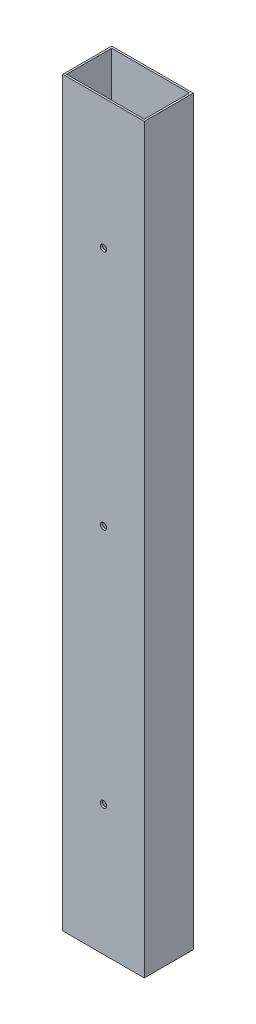
SolidWorks part; units mm, degrees
material "6061 Alloy"
ref_plane "Front Plane" through (0, 0, 0) normal (0, 0, 1) x (1, 0, 0)
ref_plane "Top Plane" through (0, 0, 0) normal (0, 1, 0) x (1, 0, 0)
ref_plane "Right Plane" through (0, 0, 0) normal (1, 0, 0) x (0, 0, -1)
sketch "Sketch1" plane through (0, 0, 0) normal (0, 1, 0) x (1, 0, 0)
  line L0 (-24.2, 14.05) -> (24.2, 14.05)
  line L1 (-25.4, -15.25) -> (25.4, -15.25)
  line L2 (-25.4, -15.25) -> (-25.4, 15.25)
  line L3 (-25.4, 15.25) -> (25.4, 15.25)
  line L4 (25.4, -15.25) -> (25.4, 15.25)
  line L5 (-25.4, -15.25) -> (25.4, 15.25) construction
  line L6 (-25.4, 15.25) -> (25.4, -15.25) construction
  line L7 (24.2, -14.05) -> (24.2, 14.05)
  line L8 (-24.2, -14.05) -> (24.2, -14.05)
  line L9 (-24.2, -14.05) -> (-24.2, 14.05)
  point P0 (0, 0)
  dimension "D1" = 50.8
  dimension "D2" = 30.5
  dimension "D3" = 1.2
extrude "Boss-Extrude1" add sketch "Sketch1" along normal blind 462
sketch "Sketch2" plane through (0, 0, -15.25) normal (0, 0, -1) x (-1, 0, 0)
  line L0 (25.4, 231) -> (-25.4, 231) construction
  line L1 (25.4, 462) -> (25.4, 0) construction
  line L2 (-25.4, 462) -> (-25.4, 0) construction
  circle A0 centre (0, 231) radius 2
  circle A1 centre (0, 381) radius 2
  circle A2 centre (0, 81) radius 2
  dimension "D1" = 4
  dimension "D2" = 4
  dimension "D3" = 4
  dimension "D4" = 150
  dimension "D5" = 150
extrude "Cut-Extrude1" cut sketch "Sketch2" against normal through all
